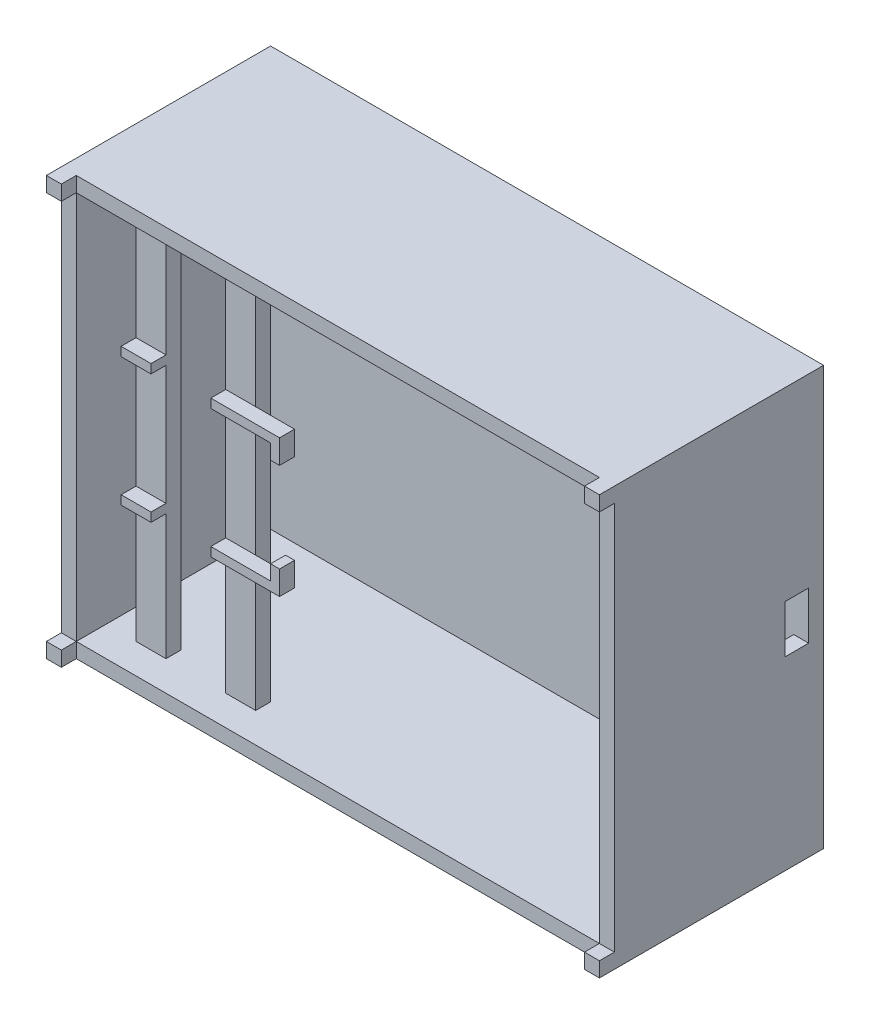
SolidWorks part; units mm, degrees
ref_plane "Front Plane" through (0, 0, 0) normal (0, 0, 1) x (1, 0, 0)
ref_plane "Top Plane" through (0, 0, 0) normal (0, 1, 0) x (1, 0, 0)
ref_plane "Right Plane" through (0, 0, 0) normal (1, 0, 0) x (0, 0, -1)
sketch "Sketch1" plane through (0, 0, 0) normal (0, 0, 1) x (1, 0, 0)
  line L1 (-92.5, -70) -> (92.5, -70)
  line L2 (-92.5, -70) -> (-92.5, 70)
  line L3 (-92.5, 70) -> (92.5, 70)
  line L4 (92.5, -70) -> (92.5, 70)
  line L5 (-92.5, -70) -> (92.5, 70) construction
  line L6 (-92.5, 70) -> (92.5, -70) construction
  point P0 (0, 0)
  dimension "D1" = 185
  dimension "D2" = 140
extrude "Boss-Extrude1" add sketch "Sketch1" along normal blind 70
shell "Shell1" thickness 5
sketch "Sketch2" plane through (0, 0, 5) normal (0, 0, 1) x (1, 0, 0)
  line L15 (-77.5, 65) -> (-77.5, -65)
  line L16 (87.5, 65) -> (-87.5, 65) construction
  line L17 (-87.5, -65) -> (87.5, -65) construction
  line L18 (-67.5, 65) -> (-67.5, -65)
  line L19 (87.5, 65) -> (-87.5, 65) construction
  line L20 (-87.5, -65) -> (87.5, -65) construction
  line L21 (-47.5, 65) -> (-47.5, -65)
  line L22 (-37.5, 65) -> (-37.5, -65)
  line L23 (-77.5, -65) -> (-67.5, -65)
  line L24 (-37.5, 65) -> (-47.5, 65)
  line L25 (-67.5, 65) -> (-77.5, 65)
  line L26 (-47.5, -65) -> (-37.5, -65)
  line L27 (-87.5, 65) -> (-87.5, -65) construction
  line L28 (-87.5, 65) -> (-87.5, -65) construction
  dimension "D1" = 10
  dimension "D2" = 10
  dimension "D3" = 10
  dimension "D4" = 50
extrude "Boss-Extrude2" add sketch "Sketch2" along normal blind 5 from offset 50
sketch "Sketch3" plane through (0, 0, 60) normal (0, 0, 1) x (1, 0, 0)
  line L0 (-47.5, 20) -> (-27.5, 20)
  line L1 (-47.5, 65) -> (-47.5, -65) construction
  line L3 (0, 0) -> (-124.3678, 0) construction
  line L4 (-47.5, -20) -> (-27.5, -20)
  line L5 (-47.5, 23) -> (-24.5, 23)
  line L7 (-47.5, -23) -> (-24.5, -23)
  line L8 (-67.5, 23) -> (-77.5, 23)
  line L9 (-67.5, -65) -> (-67.5, 65) construction
  line L10 (-77.5, 65) -> (-77.5, -65) construction
  line L11 (-67.5, 20) -> (-77.5, 20)
  line L12 (-77.5, 23) -> (-77.5, 20)
  line L13 (-67.5, 23) -> (-67.5, 20)
  line L14 (-47.5, 23) -> (-47.5, 20)
  line L15 (-47.5, -20) -> (-47.5, -23)
  line L16 (-67.5, -20) -> (-77.5, -20)
  line L17 (-67.5, -23) -> (-77.5, -23)
  line L18 (-77.5, -20) -> (-77.5, -23)
  line L19 (-67.5, -20) -> (-67.5, -23)
  line L20 (-24.5, 23) -> (-24.5, 15)
  line L21 (-24.5, 15) -> (-27.5, 15)
  line L22 (-27.5, 15) -> (-27.5, 20)
  line L23 (-27.5, -20) -> (-27.5, -15)
  line L24 (-27.5, -15) -> (-24.5, -15)
  line L25 (-24.5, -15) -> (-24.5, -23)
  line L29 (-87.5, 65) -> (-87.5, -65) construction
  point P12 (-37.5, -23)
  point P14 (0, 0)
  point P32 (-35.55, -23)
  point P33 (0, 0)
  point P35 (0, 0)
  point P36 (-27.5, -17.5)
  dimension "D1" = 40
  dimension "D2" = 3
  dimension "D3" = 3
  dimension "D4" = 3
  dimension "D5" = 8
  dimension "D6" = 3
  dimension "D7" = 8
  dimension "D8" = 60
  dimension "D9" = 60
extrude "Boss-Extrude6" add sketch "Sketch3" along normal blind 5
sketch "Sketch5" plane through (92.5, 0, 0) normal (1, 0, 0) x (0, 0, -1)
  line L0 (0, -70) -> (0, 70) construction
  line L1 (-13, -8) -> (-5, -8)
  line L2 (-13, -8) -> (-13, 8)
  line L3 (-13, 8) -> (-5, 8)
  line L4 (-5, -8) -> (-5, 8)
  line L5 (-13, -8) -> (-5, 8) construction
  line L6 (-13, 8) -> (-5, -8) construction
  line L8 (0, 0) -> (6.918, 0) construction
  point P0 (-9, 0)
  dimension "D1" = 5
  dimension "D2" = 8
  dimension "D3" = 16
extrude "Cut-Extrude1" cut sketch "Sketch5" against normal blind 5
sketch "Sketch6" plane through (0, 0, 70) normal (0, 0, 1) x (1, 0, 0)
  line L0 (-92.5, 70) -> (-92.5, -70) construction
  line L1 (-92.5, -70) -> (92.5, -70) construction
  line L2 (92.5, -70) -> (92.5, 70) construction
  line L3 (92.5, 70) -> (-92.5, 70) construction
  line L4 (-92.5, 70) -> (-92.5, 65)
  line L5 (-92.5, -70) -> (-87.5, -70)
  line L6 (92.5, -70) -> (92.5, -65)
  line L7 (92.5, 70) -> (87.5, 70)
  line L9 (-87.5, 70) -> (-87.5, 65)
  line L10 (-87.5, 65) -> (-92.5, 65)
  line L11 (87.5, 65) -> (92.5, 65)
  line L12 (87.5, 65) -> (87.5, 70)
  line L13 (-87.5, 70) -> (-92.5, 70)
  line L14 (-87.5, -65) -> (-92.5, -65)
  line L15 (-87.5, -65) -> (-87.5, -70)
  line L16 (-92.5, -65) -> (-92.5, -70)
  line L17 (87.5, -65) -> (87.5, -70)
  line L18 (87.5, -65) -> (92.5, -65)
  line L19 (87.5, -70) -> (92.5, -70)
  line L20 (92.5, 65) -> (92.5, 70)
extrude "Boss-Extrude7" add sketch "Sketch6" along normal blind 5
